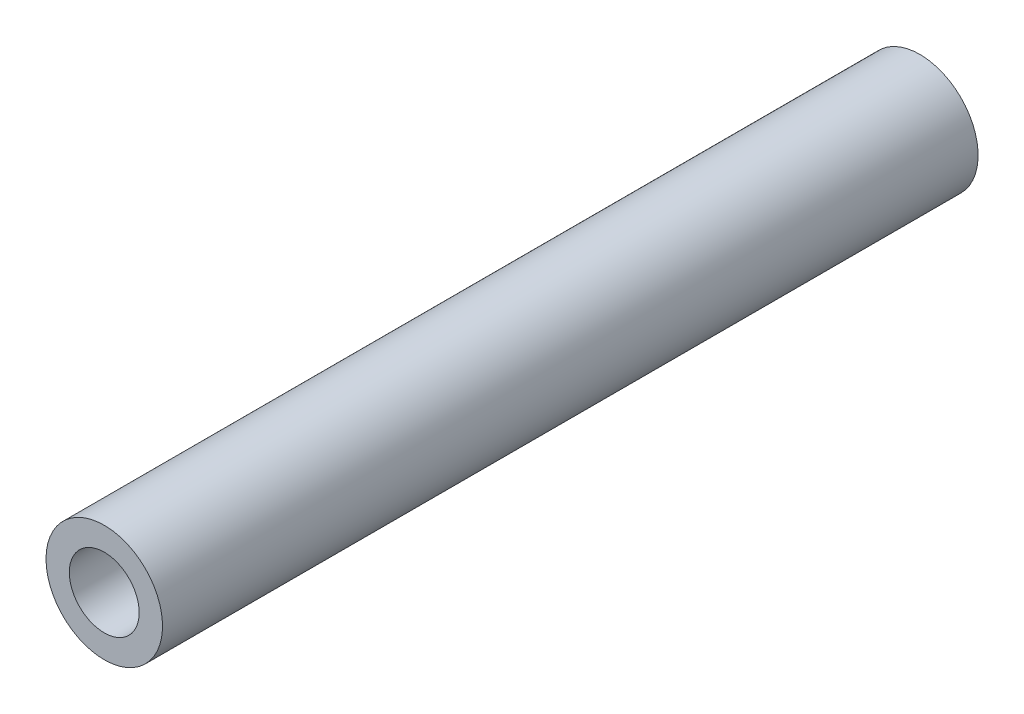
SolidWorks part; units mm, degrees
ref_plane "正面" through (0, 0, 0) normal (0, 0, 1) x (1, 0, 0)
ref_plane "平面" through (0, 0, 0) normal (0, 1, 0) x (1, 0, 0)
ref_plane "右側面" through (0, 0, 0) normal (1, 0, 0) x (0, 0, -1)
sketch "Sketch1" plane through (0, 0, 0) normal (0, 0, 1) x (1, 0, 0)
  circle A0 centre (0, 0) radius 1.5
  circle A1 centre (0, 0) radius 0.9
  dimension "D1" = 3
  dimension "D2" = 1.8
extrude "Boss-Extrude1" add sketch "Sketch1" along normal blind 21
